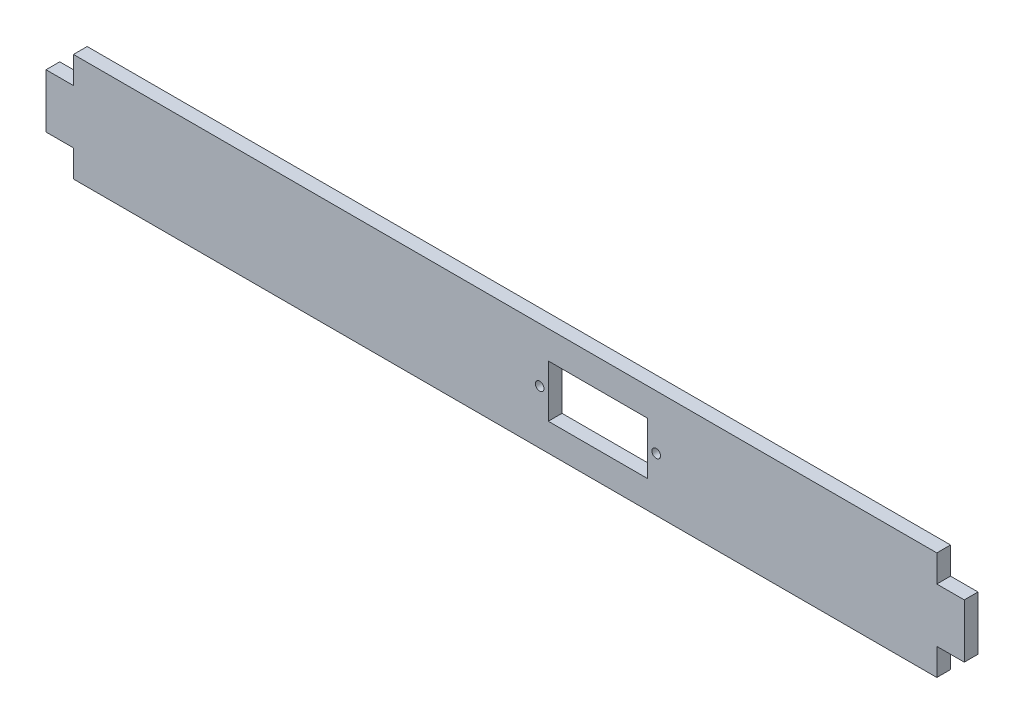
SolidWorks part; units mm, degrees
ref_plane "Front Plane" through (0, 0, 0) normal (0, 0, 1) x (1, 0, 0)
ref_plane "Top Plane" through (0, 0, 0) normal (0, 1, 0) x (1, 0, 0)
ref_plane "Right Plane" through (0, 0, 0) normal (1, 0, 0) x (0, 0, -1)
sketch "Sketch2" plane through (0, 0, 0) normal (0, 0, 1) x (1, 0, 0)
  line L1 (0, 0) -> (200, 0)
  line L2 (0, 0) -> (0, 25)
  line L3 (0, 25) -> (200, 25)
  line L4 (200, 0) -> (200, 25)
  dimension "D1" = 200
  dimension "D2" = 25
extrude "Boss-Extrude1" add sketch "Sketch2" along normal mid plane 3.18
sketch "Sketch4" plane through (0, 0, -1.59) normal (0, 0, -1) x (-1, 0, 0)
  line L0 (-121.5, 18.5075) -> (-121.5, 6.4075) construction
  line L1 (-133, 18.5075) -> (-110, 18.5075)
  line L2 (-133, 18.5075) -> (-133, 6.4075)
  line L3 (-133, 6.4075) -> (-110, 6.4075)
  line L4 (-110, 18.5075) -> (-110, 6.4075)
  line L5 (0, 25) -> (0, 0) construction
  circle A2 centre (-135, 12.4575) radius 1
  circle A3 centre (-108, 12.4575) radius 1
  dimension "D3" = 2
  dimension "D4" = 2
  dimension "D1" = 23
  dimension "D2" = 12.1
  dimension "D5" = 110
extrude "Cut-Extrude1" cut sketch "Sketch4" against normal blind 3.18
sketch "Sketch5" plane through (0, 0, -1.59) normal (0, 0, -1) x (-1, 0, 0)
  line L5 (-200, 0) -> (-200, 25) construction
  line L6 (-200, 18.75) -> (-206.36, 18.75)
  line L7 (-200, 18.75) -> (-200, 6.25)
  line L8 (-200, 6.25) -> (-206.36, 6.25)
  line L9 (-206.36, 18.75) -> (-206.36, 6.25)
  line L10 (0, 0) -> (-200, 0) construction
  line L11 (-100, 25) -> (-100, 0) construction
  line L12 (-200, 25) -> (0, 25) construction
  line L13 (0, 12.5) -> (-200, 12.5) construction
  line L14 (0, 25) -> (0, 0) construction
  line L15 (0, 6.25) -> (6.36, 6.25)
  line L16 (6.36, 18.75) -> (6.36, 6.25)
  line L17 (0, 18.75) -> (6.36, 18.75)
  line L18 (0, 18.75) -> (0, 6.25)
  dimension "D1" = 12.5
  dimension "D2" = 6.36
extrude "Boss-Extrude2" add sketch "Sketch5" against normal blind 3.18
equation "\"Acrylic Sheet Thickness\"= 3.18mm"
equation "\"D1@Sketch5\"=25/2"
